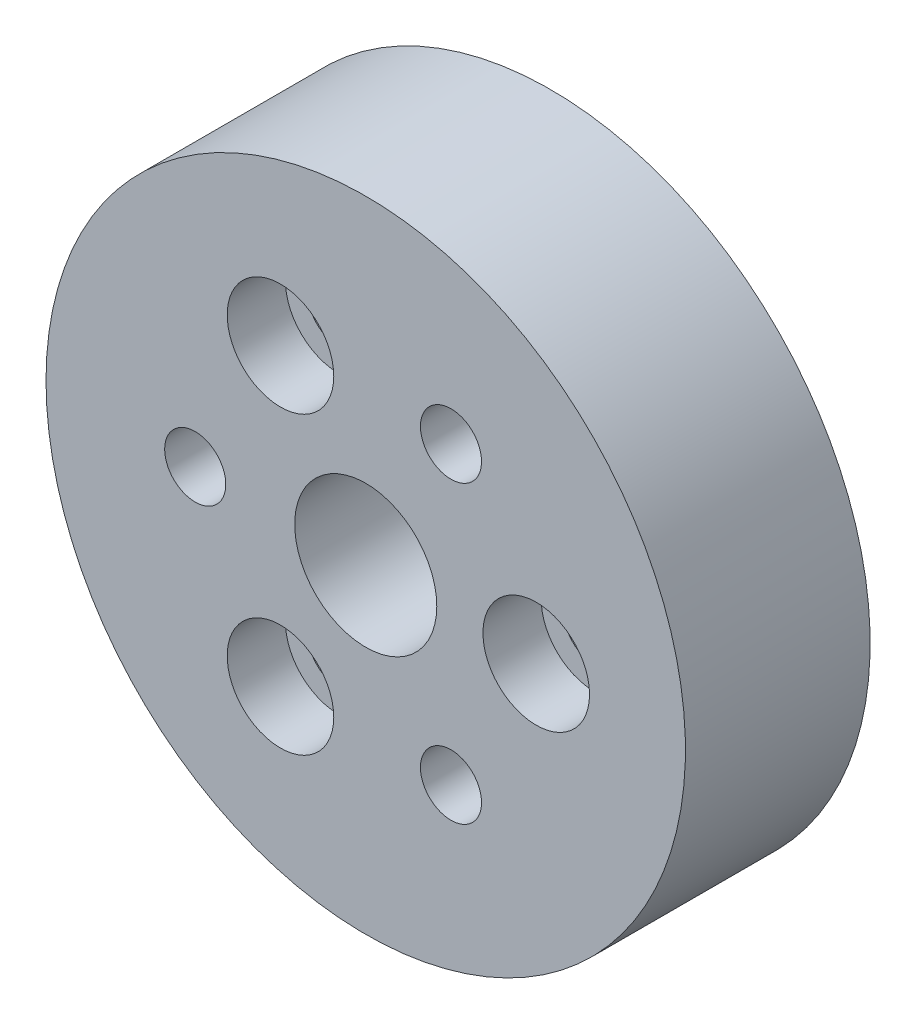
SolidWorks part; units mm, degrees
material "ABS"
ref_plane "Front Plane" through (0, 0, 0) normal (0, 0, 1) x (1, 0, 0)
ref_plane "Top Plane" through (0, 0, 0) normal (0, 1, 0) x (1, 0, 0)
ref_plane "Right Plane" through (0, 0, 0) normal (1, 0, 0) x (0, 0, -1)
sketch "Sketch2" plane through (0, 0, 0) normal (0, 0, 1) x (1, 0, 0)
  line L1 (0, 0) -> (141.7182, 0) construction
  circle A0 centre (0, 0) radius 22.5
  circle A2 centre (12, 0) radius 2.15
  circle A3 centre (6, -10.3923) radius 2.15
  circle A4 centre (-6, -10.3923) radius 2.15
  circle A5 centre (-12, 0) radius 2.15
  circle A6 centre (-6, 10.3923) radius 2.15
  circle A7 centre (6, 10.3923) radius 2.15
  point P21 (0, 0)
  dimension "D1" = 45
  dimension "D2" = 4.3
  dimension "D3" = 12
  dimension "D4" = 6
extrude "Boss-Extrude1" add sketch "Sketch2" along normal blind 13
sketch "Sketch3" plane through (0, 0, 13) normal (0, 0, 1) x (1, 0, 0)
  circle A0 centre (-6, 10.3923) radius 3.75
  circle A1 centre (-6, -10.3923) radius 3.75
  circle A2 centre (12, 0) radius 3.75
  dimension "D1" = 7.5
  dimension "D2" = 7.5
  dimension "D3" = 7.5
extrude "Cut-Extrude1" cut sketch "Sketch3" against normal blind 4.1
sketch "Sketch5" plane through (0, 0, 13) normal (0, 0, 1) x (1, 0, 0)
  circle A0 centre (0, 0) radius 5
  dimension "D1" = 10
extrude "Cut-Extrude3" cut sketch "Sketch5" against normal through all
equation "\"cybergearOutput\"=45"
equation "\"D1@Sketch2\"=\"cybergearOutput\""
equation "\"thighLength\"=185"
equation "\"legLength\"=200"
equation "\"m3Thru\"=3.2"
equation "\"m4Thru\"=4.3"
equation "\"shoulder5mm\"=5.1"
equation "\"6706out\"=37.125"
equation "\"6706in\"=30"
equation "\"6904out\"=30.125"
equation "\"6904in\"=17"
equation "\"D2@Sketch2\"=\"m4Thru\""
equation "\"m3Insert\"=4.2"
equation "\"m4Insert\"=5.3"
